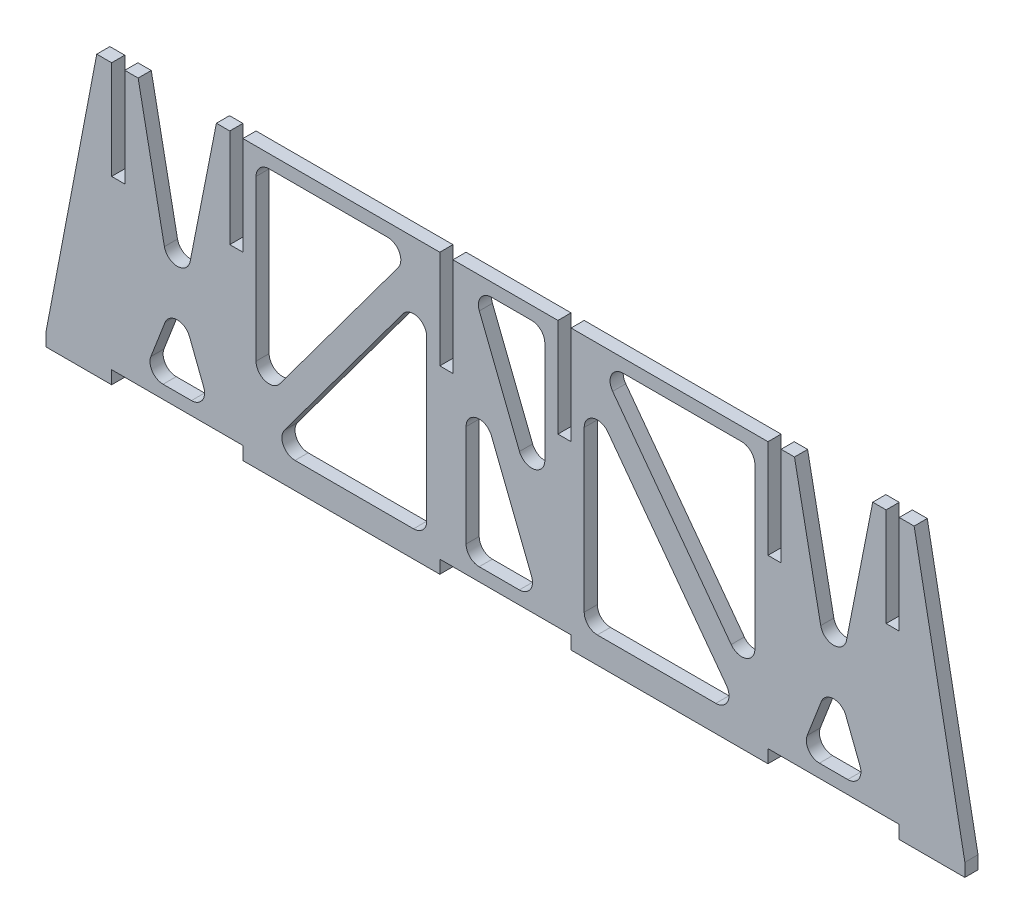
SolidWorks part; units mm, degrees
material "AISI 4340 Steel, normalized"
ref_plane "Front Plane" through (0, 0, 0) normal (0, 0, 1) x (1, 0, 0)
ref_plane "Top Plane" through (0, 0, 0) normal (0, 1, 0) x (1, 0, 0)
ref_plane "Right Plane" through (0, 0, 0) normal (1, 0, 0) x (0, 0, -1)
sketch "Sketch1" plane through (0, 0, 0) normal (0, 0, 1) x (1, 0, 0)
  line B0 (-6.1189, 0) -> (6.1189, 0)
  line B1 (-10.1189, 34.977) -> (-10.1189, 4)
  line B2 (9.8391, 5.4697) -> (-2.3987, 36.4467)
  line B3 (9.8811, 73) -> (-2.3568, 73)
  line B4 (13.8811, 38.023) -> (13.8811, 69)
  line B5 (141.8811, -8) -> (141.8811, -4)
  line B6 (141.8811, -4) -> (126.4209, 77)
  line B7 (126.4209, 77) -> (121.8811, 77)
  line B8 (121.8811, 77) -> (121.8811, 17)
  line B9 (121.8811, 17) -> (117.8811, 17)
  line B10 (117.8811, 17) -> (117.8811, 77)
  line B11 (117.8811, 77) -> (113.8038, 77)
  line B12 (113.8038, 77) -> (105.8053, 36.5074)
  line B13 (97.9569, 36.5074) -> (89.9584, 77)
  line B14 (89.9584, 77) -> (85.8811, 77)
  line B15 (85.8811, 77) -> (85.8811, 17)
  line B16 (85.8811, 17) -> (81.8811, 17)
  line B17 (81.8811, 17) -> (81.8811, 77)
  line B18 (81.8811, 77) -> (-78.1189, 77)
  line B19 (-78.1189, 77) -> (-78.1189, 17)
  line B20 (-78.1189, 17) -> (-82.1189, 17)
  line B21 (-82.1189, 17) -> (-82.1189, 77)
  line B22 (-82.1189, 77) -> (-86.1962, 77)
  line B23 (-86.1962, 77) -> (-94.1947, 36.5074)
  line B24 (-102.0431, 36.5074) -> (-110.0416, 77)
  line B25 (-110.0416, 77) -> (-114.1189, 77)
  line B26 (-114.1189, 77) -> (-114.1189, 17)
  line B27 (-114.1189, 17) -> (-118.1189, 17)
  line B28 (-118.1189, 17) -> (-118.1189, 77)
  line B29 (-118.1189, 77) -> (-122.6588, 77)
  line B30 (-122.6588, 77) -> (-138.1189, -4)
  line B31 (-138.1189, -4) -> (-138.1189, -8)
  line B32 (-138.1189, -8) -> (141.8811, -8)
  line B33 (-102.4385, 0) -> (-93.7993, 0)
  line B34 (-101.8486, 16.5907) -> (-106.1682, 5.4455)
  line B35 (-90.0697, 5.4455) -> (-94.3892, 16.5907)
  line B36 (-74.1189, 69) -> (-74.1189, 20.2402)
  line B37 (-34.0006, 73) -> (-70.1189, 73)
  line B38 (-66.9047, 17.8593) -> (-30.7863, 66.6191)
  line B39 (-22.1189, 4) -> (-22.1189, 52.7598)
  line B40 (-62.2373, 0) -> (-26.1189, 0)
  line B41 (-29.3331, 55.1407) -> (-65.4515, 6.3809)
  line B42 (-6.077, 67.5303) -> (6.1609, 36.5533)
  arc B43 (97.9569, 36.5074) -> (105.8053, 36.5074) centre (101.8811, 37.2826) ccw
  arc B44 (-102.0431, 36.5074) -> (-94.1947, 36.5074) centre (-98.1189, 37.2826) ccw
  arc B45 (-10.1189, 4) -> (-6.1189, 0) centre (-6.1189, 4) ccw
  arc B46 (-2.3987, 36.4467) -> (-10.1189, 34.977) centre (-6.1189, 34.977) ccw
  arc B47 (6.1189, 0) -> (9.8391, 5.4697) centre (6.1189, 4) ccw
  arc B48 (13.8811, 69) -> (9.8811, 73) centre (9.8811, 69) ccw
  arc B49 (6.1609, 36.5533) -> (13.8811, 38.023) centre (9.8811, 38.023) ccw
  arc B50 (-93.7993, 0) -> (-90.0697, 5.4455) centre (-93.7993, 4) ccw
  arc B51 (-106.1682, 5.4455) -> (-102.4385, 0) centre (-102.4385, 4) ccw
  arc B52 (-94.3892, 16.5907) -> (-101.8486, 16.5907) centre (-98.1189, 15.1452) ccw
  arc B53 (-70.1189, 73) -> (-74.1189, 69) centre (-70.1189, 69) ccw
  arc B54 (-30.7863, 66.6191) -> (-34.0006, 73) centre (-34.0006, 69) ccw
  arc B55 (-74.1189, 20.2402) -> (-66.9047, 17.8593) centre (-70.1189, 20.2402) ccw
  arc B56 (-26.1189, 0) -> (-22.1189, 4) centre (-26.1189, 4) ccw
  arc B57 (-65.4515, 6.3809) -> (-62.2373, 0) centre (-62.2373, 4) ccw
  arc B58 (-22.1189, 52.7598) -> (-29.3331, 55.1407) centre (-26.1189, 52.7598) ccw
  arc B59 (-2.3568, 73) -> (-6.077, 67.5303) centre (-2.3568, 69) ccw
sketch_block_instance "Block-pedalbox back-1"
sketch_block "Block-pedalbox back"
sketch "Sketch2" plane through (0, 0, 0) normal (0, 0, 1) x (1, 0, 0)
  line L0 (1.8811, 77) -> (1.8811, -8) construction
  line L1 (-6.1189, 0) -> (6.1189, 0) construction
  line L2 (-102.4385, 0) -> (-93.7993, 0) construction
  line L3 (-90.0697, 5.4455) -> (-94.3892, 16.5907) construction
  line L4 (-101.8486, 16.5907) -> (-106.1682, 5.4455) construction
  line L5 (-138.1189, -4) -> (-138.1189, -8) construction
  line L6 (-138.1189, -8) -> (141.8811, -8) construction
  line L7 (141.8811, -8) -> (141.8811, -4) construction
  line L8 (141.8811, -4) -> (126.4209, 77) construction
  line L9 (126.4209, 77) -> (121.8811, 77) construction
  line L10 (121.8811, 77) -> (121.8811, 17) construction
  line L12 (117.8811, 17) -> (117.8811, 77) construction
  line L13 (117.8811, 77) -> (113.8038, 77) construction
  line L14 (113.8038, 77) -> (105.8053, 36.5074) construction
  line L15 (97.9569, 36.5074) -> (89.9584, 77) construction
  line L16 (89.9584, 77) -> (85.8811, 77) construction
  line L17 (85.8811, 77) -> (85.8811, 17) construction
  line L19 (81.8811, 17) -> (81.8811, 77) construction
  line L20 (81.8811, 77) -> (-78.1189, 77) construction
  line L21 (-78.1189, 77) -> (-78.1189, 17) construction
  line L23 (-82.1189, 17) -> (-82.1189, 77) construction
  line L24 (-82.1189, 77) -> (-86.1962, 77) construction
  line L25 (-86.1962, 77) -> (-94.1947, 36.5074) construction
  line L26 (-102.0431, 36.5074) -> (-110.0416, 77) construction
  line L27 (-110.0416, 77) -> (-114.1189, 77) construction
  line L28 (-114.1189, 77) -> (-114.1189, 17) construction
  line L30 (-118.1189, 17) -> (-118.1189, 77) construction
  line L31 (-118.1189, 77) -> (-122.6588, 77) construction
  line L32 (-122.6588, 77) -> (-138.1189, -4) construction
  line L33 (-22.1189, 4) -> (-22.1189, 52.7598) construction
  line L34 (-29.3331, 55.1407) -> (-65.4515, 6.3809) construction
  line L35 (-62.2373, 0) -> (-26.1189, 0) construction
  line L36 (-34.0006, 73) -> (-70.1189, 73) construction
  line L37 (-74.1189, 69) -> (-74.1189, 20.2402) construction
  line L38 (-66.9047, 17.8593) -> (-30.7863, 66.6191) construction
  line L39 (9.8811, 73) -> (-2.3568, 73) construction
  line L40 (-6.077, 67.5303) -> (6.1609, 36.5533) construction
  line L41 (13.8811, 38.023) -> (13.8811, 69) construction
  line L42 (-10.1189, 34.977) -> (-10.1189, 4) construction
  line L43 (9.8391, 5.4697) -> (-2.3987, 36.4467) construction
  line L44 (-102.4385, 0) -> (-93.7993, 0)
  line L45 (-90.0697, 5.4455) -> (-94.3892, 16.5907)
  line L46 (-101.8486, 16.5907) -> (-106.1682, 5.4455)
  line L47 (-138.1189, -4) -> (-138.1189, -8)
  line L48 (-138.1189, -8) -> (-118.1189, -8)
  line L49 (141.8811, -8) -> (141.8811, -4)
  line L50 (141.8811, -4) -> (126.4209, 77)
  line L51 (126.4209, 77) -> (121.8811, 77)
  line L52 (121.8811, 77) -> (121.8811, 47)
  line L54 (117.8811, 47) -> (117.8811, 77)
  line L55 (117.8811, 77) -> (113.8038, 77)
  line L56 (113.8038, 77) -> (105.8053, 36.5074)
  line L57 (97.9569, 36.5074) -> (89.9584, 77)
  line L58 (89.9584, 77) -> (85.8811, 77)
  line L59 (85.8811, 77) -> (85.8811, 47)
  line L61 (81.8811, 47) -> (81.8811, 77)
  line L62 (81.8811, 77) -> (21.8811, 77)
  line L63 (-78.1189, 77) -> (-78.1189, 47)
  line L65 (-82.1189, 47) -> (-82.1189, 77)
  line L66 (-82.1189, 77) -> (-86.1962, 77)
  line L67 (-86.1962, 77) -> (-94.1947, 36.5074)
  line L68 (-102.0431, 36.5074) -> (-110.0416, 77)
  line L69 (-110.0416, 77) -> (-114.1189, 77)
  line L70 (-114.1189, 77) -> (-114.1189, 47)
  line L72 (-118.1189, 47) -> (-118.1189, 77)
  line L73 (-118.1189, 77) -> (-122.6588, 77)
  line L74 (-122.6588, 77) -> (-138.1189, -4)
  line L75 (-22.1189, 4) -> (-22.1189, 52.7598)
  line L76 (-29.3331, 55.1407) -> (-65.4515, 6.3809)
  line L77 (-62.2373, 0) -> (-26.1189, 0)
  line L78 (-34.0006, 73) -> (-70.1189, 73)
  line L79 (-74.1189, 69) -> (-74.1189, 20.2402)
  line L80 (-66.9047, 17.8593) -> (-30.7863, 66.6191)
  line L81 (9.8811, 73) -> (-2.3568, 73)
  line L82 (-6.077, 67.5303) -> (6.1609, 36.5533)
  line L83 (13.8811, 38.023) -> (13.8811, 69)
  line L84 (-6.1189, 0) -> (6.1189, 0)
  line L85 (-10.1189, 34.977) -> (-10.1189, 4)
  line L86 (9.8391, 5.4697) -> (-2.3987, 36.4467)
  line L87 (-118.1189, 47) -> (-114.1189, 47)
  line L88 (-82.1189, 47) -> (-78.1189, 47)
  line L89 (81.8811, 47) -> (85.8811, 47)
  line L90 (117.8811, 47) -> (121.8811, 47)
  line L91 (105.6108, 16.5907) -> (109.9303, 5.4455)
  line L92 (93.8318, 5.4455) -> (98.1514, 16.5907)
  line L93 (106.2007, 0) -> (97.5615, 0)
  line L94 (70.6669, 17.8593) -> (34.5485, 66.6191)
  line L95 (77.8811, 69) -> (77.8811, 20.2402)
  line L96 (37.7627, 73) -> (73.8811, 73)
  line L97 (65.9994, 0) -> (29.8811, 0)
  line L98 (33.0953, 55.1407) -> (69.2137, 6.3809)
  line L99 (25.8811, 4) -> (25.8811, 52.7598)
  line L100 (-18.1189, 47) -> (-18.1189, 77)
  line L101 (-18.1189, 47) -> (-14.1189, 47)
  line L102 (-14.1189, 77) -> (-14.1189, 47)
  line L103 (17.8811, 47) -> (17.8811, 77)
  line L104 (17.8811, 47) -> (21.8811, 47)
  line L105 (21.8811, 77) -> (21.8811, 47)
  line L106 (-18.1189, 77) -> (-78.1189, 77)
  line L107 (17.8811, 77) -> (-14.1189, 77)
  line L108 (21.8811, -4) -> (-18.1189, -4)
  line L109 (-18.1189, -4) -> (-18.1189, -8)
  line L110 (-78.1189, -8) -> (-78.1189, -4)
  line L111 (-78.1189, -4) -> (-118.1189, -4)
  line L112 (-118.1189, -4) -> (-118.1189, -8)
  line L113 (21.8811, -4) -> (21.8811, -8)
  line L114 (121.8811, -4) -> (121.8811, -8)
  line L115 (81.8811, -4) -> (121.8811, -4)
  line L116 (81.8811, -8) -> (81.8811, -4)
  line L117 (-78.1189, -8) -> (-18.1189, -8)
  line L118 (21.8811, -8) -> (81.8811, -8)
  line L119 (121.8811, -8) -> (141.8811, -8)
  line L120 (-18.1189, -8) -> (21.8811, -8) construction
  arc A0 (-93.7993, 0) -> (-90.0697, 5.4455) centre (-93.7993, 4) ccw construction
  arc A1 (-94.3892, 16.5907) -> (-101.8486, 16.5907) centre (-98.1189, 15.1452) ccw construction
  arc A2 (-106.1682, 5.4455) -> (-102.4385, 0) centre (-102.4385, 4) ccw construction
  arc A3 (97.9569, 36.5074) -> (105.8053, 36.5074) centre (101.8811, 37.2826) ccw construction
  arc A4 (-102.0431, 36.5074) -> (-94.1947, 36.5074) centre (-98.1189, 37.2826) ccw construction
  arc A5 (-22.1189, 52.7598) -> (-29.3331, 55.1407) centre (-26.1189, 52.7598) ccw construction
  arc A6 (-65.4515, 6.3809) -> (-62.2373, 0) centre (-62.2373, 4) ccw construction
  arc A7 (-26.1189, 0) -> (-22.1189, 4) centre (-26.1189, 4) ccw construction
  arc A8 (-70.1189, 73) -> (-74.1189, 69) centre (-70.1189, 69) ccw construction
  arc A9 (-74.1189, 20.2402) -> (-66.9047, 17.8593) centre (-70.1189, 20.2402) ccw construction
  arc A10 (-30.7863, 66.6191) -> (-34.0006, 73) centre (-34.0006, 69) ccw construction
  arc A11 (-2.3568, 73) -> (-6.077, 67.5303) centre (-2.3568, 69) ccw construction
  arc A12 (6.1609, 36.5533) -> (13.8811, 38.023) centre (9.8811, 38.023) ccw construction
  arc A13 (13.8811, 69) -> (9.8811, 73) centre (9.8811, 69) ccw construction
  arc A14 (-10.1189, 4) -> (-6.1189, 0) centre (-6.1189, 4) ccw construction
  arc A15 (-2.3987, 36.4467) -> (-10.1189, 34.977) centre (-6.1189, 34.977) ccw construction
  arc A16 (6.1189, 0) -> (9.8391, 5.4697) centre (6.1189, 4) ccw construction
  arc A17 (-93.7993, 0) -> (-90.0697, 5.4455) centre (-93.7993, 4) ccw
  arc A18 (-94.3892, 16.5907) -> (-101.8486, 16.5907) centre (-98.1189, 15.1452) ccw
  arc A19 (-106.1682, 5.4455) -> (-102.4385, 0) centre (-102.4385, 4) ccw
  arc A20 (97.9569, 36.5074) -> (105.8053, 36.5074) centre (101.8811, 37.2826) ccw
  arc A21 (-102.0431, 36.5074) -> (-94.1947, 36.5074) centre (-98.1189, 37.2826) ccw
  arc A22 (-22.1189, 52.7598) -> (-29.3331, 55.1407) centre (-26.1189, 52.7598) ccw
  arc A23 (-65.4515, 6.3809) -> (-62.2373, 0) centre (-62.2373, 4) ccw
  arc A24 (-26.1189, 0) -> (-22.1189, 4) centre (-26.1189, 4) ccw
  arc A25 (-70.1189, 73) -> (-74.1189, 69) centre (-70.1189, 69) ccw
  arc A26 (-74.1189, 20.2402) -> (-66.9047, 17.8593) centre (-70.1189, 20.2402) ccw
  arc A27 (-30.7863, 66.6191) -> (-34.0006, 73) centre (-34.0006, 69) ccw
  arc A28 (-2.3568, 73) -> (-6.077, 67.5303) centre (-2.3568, 69) ccw
  arc A29 (6.1609, 36.5533) -> (13.8811, 38.023) centre (9.8811, 38.023) ccw
  arc A30 (13.8811, 69) -> (9.8811, 73) centre (9.8811, 69) ccw
  arc A31 (-10.1189, 4) -> (-6.1189, 0) centre (-6.1189, 4) ccw
  arc A32 (-2.3987, 36.4467) -> (-10.1189, 34.977) centre (-6.1189, 34.977) ccw
  arc A33 (6.1189, 0) -> (9.8391, 5.4697) centre (6.1189, 4) ccw
  arc A34 (109.9303, 5.4455) -> (106.2007, 0) centre (106.2007, 4) cw
  arc A35 (98.1514, 16.5907) -> (105.6108, 16.5907) centre (101.8811, 15.1452) cw
  arc A36 (97.5615, 0) -> (93.8318, 5.4455) centre (97.5615, 4) cw
  arc A37 (34.5485, 66.6191) -> (37.7627, 73) centre (37.7627, 69) cw
  arc A38 (77.8811, 20.2402) -> (70.6669, 17.8593) centre (73.8811, 20.2402) cw
  arc A39 (73.8811, 73) -> (77.8811, 69) centre (73.8811, 69) cw
  arc A40 (29.8811, 0) -> (25.8811, 4) centre (29.8811, 4) cw
  arc A41 (69.2137, 6.3809) -> (65.9994, 0) centre (65.9994, 4) cw
  arc A42 (25.8811, 52.7598) -> (33.0953, 55.1407) centre (29.8811, 52.7598) cw
  point P130 (1.8811, -4)
  dimension "D1" = 30
  dimension "D3" = 16
  dimension "D4" = 20
  dimension "D5" = 40
  dimension "D6" = 60
  dimension "D2" = 2
extrude "Boss-Extrude1" add sketch "Sketch2" along normal blind 4
